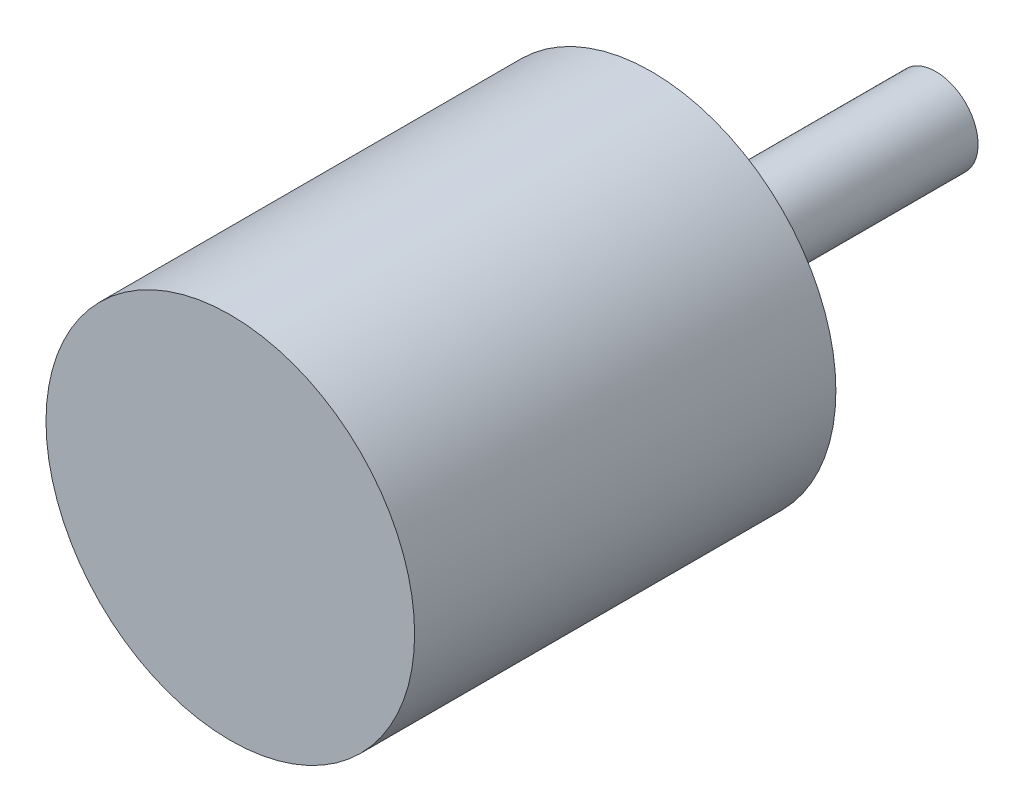
SolidWorks part; units mm, degrees
ref_plane "Front Plane" through (0, 0, 0) normal (0, 0, 1) x (1, 0, 0)
ref_plane "Top Plane" through (0, 0, 0) normal (0, 1, 0) x (1, 0, 0)
ref_plane "Right Plane" through (0, 0, 0) normal (1, 0, 0) x (0, 0, -1)
sketch "Sketch1" plane through (0, 0, 0) normal (0, 0, 1) x (1, 0, 0)
  circle A0 centre (0, 0) radius 17.5
  dimension "D1" = 35
extrude "Boss-Extrude1" add sketch "Sketch1" along normal blind 40
sketch "Sketch2" plane through (0, 0, 0) normal (0, 0, -1) x (-1, 0, 0)
  circle A0 centre (0, 0) radius 2
  dimension "D1" = 4
extrude "Boss-Extrude2" add sketch "Sketch2" along normal blind 17
sketch "Sketch3" plane through (0, 0, -17) normal (0, 0, -1) x (-1, 0, 0)
  circle A2 centre (0, 0) radius 4
  circle A3 centre (0, 0) radius 4
  dimension "D1" = 2
extrude "Boss-Extrude3" add sketch "Sketch3" along normal blind 10 and the other way blind 10
